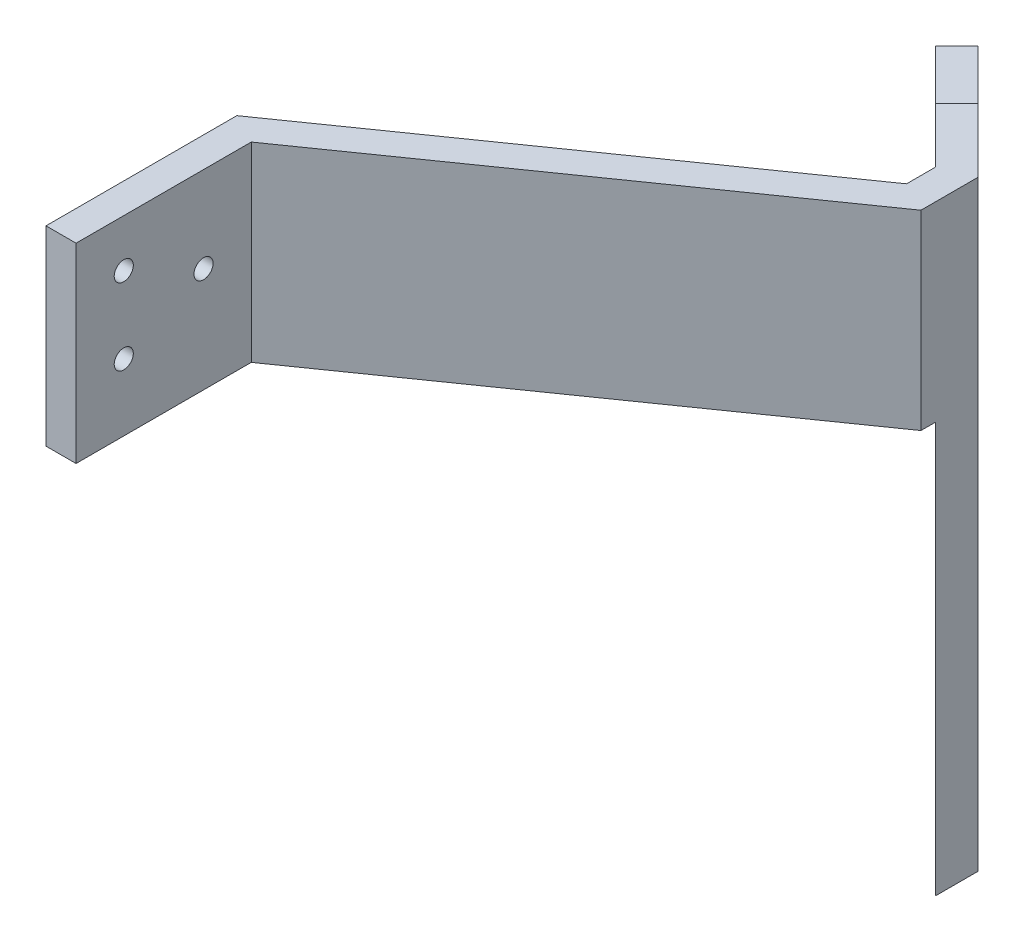
SolidWorks part; units mm, degrees
ref_plane "Front Plane" through (0, 0, 0) normal (0, 0, 1) x (1, 0, 0)
ref_plane "Top Plane" through (0, 0, 0) normal (0, 1, 0) x (1, 0, 0)
ref_plane "Right Plane" through (0, 0, 0) normal (1, 0, 0) x (0, 0, -1)
sketch "Sketch1" plane through (0, 0, 0) normal (0, 1, 0) x (1, 0, 0)
  line L0 (0, 0) -> (0, 31.75)
  line L1 (0, 31.75) -> (65.5322, 77.6361)
  line L2 (65.5322, 77.6361) -> (65.5322, 82.4523)
  line L3 (65.5322, 82.4523) -> (56.39, 91.5944)
  line L4 (56.39, 91.5944) -> (59.9256, 95.13)
  line L5 (59.9256, 95.13) -> (70.5322, 84.5234)
  line L6 (70.5322, 84.5234) -> (70.5322, 75.0333)
  line L7 (70.5322, 75.0333) -> (5, 29.1472)
  line L8 (5, 29.1472) -> (5, 0)
  line L9 (5, 0) -> (0, 0)
  dimension "D1" = 31.75
  dimension "D2" = 5
  dimension "D3" = 80
  dimension "D4" = 125
  dimension "D5" = 5
  dimension "D6" = 5
  dimension "D7" = 5
  dimension "D8" = 15
  dimension "D9" = 80
  dimension "D10" = 70.5322
extrude "ProfileBoss-Extrude1" add sketch "Sketch1" along normal blind 31.75
sketch "Sketch2" plane through (0, 0, 0) normal (0, -1, 0) x (1, 0, 0)
  line L0 (59.9256, -95.13) -> (70.5322, -84.5234)
  line L3 (59.9256, -95.13) -> (56.39, -91.5944)
  line L4 (56.39, -91.5944) -> (65.5322, -82.4523)
  line L5 (65.5322, -82.4523) -> (70.5322, -77.4523)
  line L6 (70.5322, -75.0333) -> (70.5322, -84.5234) construction
  line L7 (70.5322, -77.4523) -> (70.5322, -84.5234)
extrude "RightProfileBoss-Extrude2" add sketch "Sketch2" along normal blind 68.25
sketch "Sketch6" plane through (-17.6022, 0, -17.6022) normal (-0.7071, 0, -0.7071) x (-0.7071, 0, 0.7071)
  line L0 (-104.6408, 31.75) -> (-104.6408, -68.25) construction
  line L1 (-109.6408, -68.25) -> (-104.6408, -68.25)
  line L2 (-109.6408, -68.25) -> (-109.6408, -5.9247)
  line L3 (-109.6408, -5.9247) -> (-104.6408, -5.9247)
  line L4 (-104.6408, -68.25) -> (-104.6408, -5.9247)
  dimension "D1" = 62.3253
extrude "TopProfileBoss-Extrude5" add sketch "Sketch6" along normal blind 65
sketch "Sketch7" plane through (77.5278, 0, -77.5278) normal (0.7071, 0, -0.7071) x (-0.7071, 0, -0.7071)
  line L0 (89.8933, -5.9247) -> (89.8933, -68.25) construction
  line L1 (89.8933, -68.25) -> (9.8933, -68.25) construction
  circle A0 centre (82.8933, -11.25) radius 2.25
  circle A1 centre (57.8933, -11.25) radius 2.25
  circle A2 centre (82.8933, -61.25) radius 2.25
  circle A3 centre (57.8933, -61.25) radius 2.25
  dimension "D1" = 4.5
  dimension "D2" = 50
  dimension "D3" = 25
  dimension "D4" = 7
  dimension "D5" = 7
extrude "HDMI HolesCut-Extrude1" cut sketch "Sketch7" against normal through all
sketch "Sketch8" plane through (5, 0, 0) normal (1, 0, 0) x (0, 0, -1)
  line L0 (0, 31.75) -> (0, 0) construction
  line L1 (29.1472, 31.75) -> (29.1472, 0) construction
  line L2 (0, 0) -> (29.1472, 0) construction
  line L3 (0, 31.75) -> (29.1472, 31.75) construction
  circle A0 centre (7.9375, 23.8125) radius 1.5875
  circle A1 centre (21.2097, 17.4625) radius 1.5875
  circle A2 centre (7.9375, 11.1125) radius 1.5875
  dimension "D2" = 3.175
  dimension "D1" = 7.9375
  dimension "D3" = 7.9375
  dimension "D4" = 11.1125
  dimension "D5" = 7.9375
  dimension "D6" = 17.4625
extrude "MountHolesCut-Extrude2" cut sketch "Sketch8" against normal through all
sketch "Sketch9" plane through (77.5278, 0, -77.5278) normal (0.7071, 0, -0.7071) x (-0.7071, 0, -0.7071)
  circle A0 centre (57.8933, -11.25) radius 2.6
  circle A1 centre (82.8933, -11.25) radius 2.6
  circle A2 centre (82.8933, -61.25) radius 2.6
  circle A3 centre (57.8933, -61.25) radius 2.6
  dimension "D1" = 5.2
extrude "HDMIBoreCut-Extrude3" cut sketch "Sketch9" against normal blind 1
equation "\"D1@Sketch8\"=3.175*2.5"
equation "\"D3@Sketch8\"=3.175*2.5"
equation "\"D4@Sketch8\"=3.175*3.5"
equation "\"D5@Sketch8\"=3.175*2.5"
equation "\"D6@Sketch8\"=1.25in/2 + 3.175mm/2"
equation "\"D1@RightProfileBoss-Extrude2\"=100mm - 1.25in"
equation "\"HDMIMountHoleXDistance\"=50"
equation "\"D2@Sketch7\"=\"HDMIMountHoleXDistance\""
equation "\"HDMIMountHolYDistance\"=25"
equation "\"D3@Sketch7\"=\"HDMIMountHolYDistance\""
